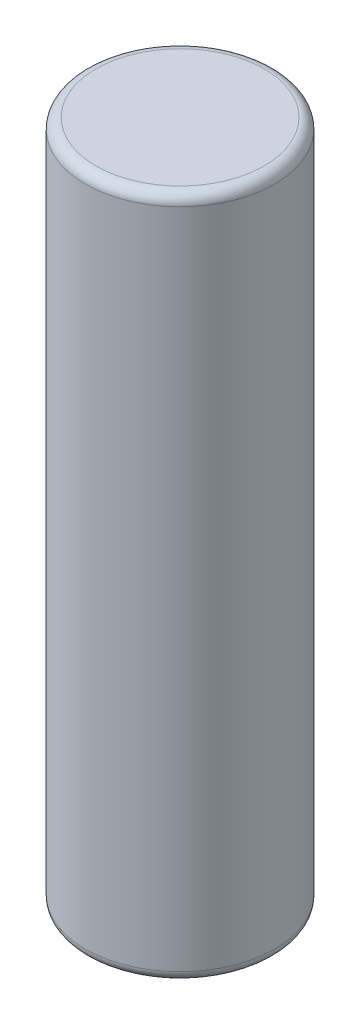
SolidWorks part; units mm, degrees
ref_plane "Front Plane" through (0, 0, 0) normal (0, 0, 1) x (1, 0, 0)
ref_plane "Top Plane" through (0, 0, 0) normal (0, 1, 0) x (1, 0, 0)
ref_plane "Right Plane" through (0, 0, 0) normal (1, 0, 0) x (0, 0, -1)
sketch "Sketch1" plane through (0, 871.7098, 0) normal (0, 1, 0) x (1, 0, 0)
  circle A0 centre (366.9989, 847.8745) radius 90
  circle A1 centre (366.9989, 847.8745) radius 90 construction
extrude "Boss-Extrude1" add sketch "Sketch1" against normal blind 600 and the other way blind 50 contours A0
fillet "Fillet1" radius 10 2 edges at (366.9989, 921.7098, -757.8745) (366.9989, 271.7098, -757.8745)
